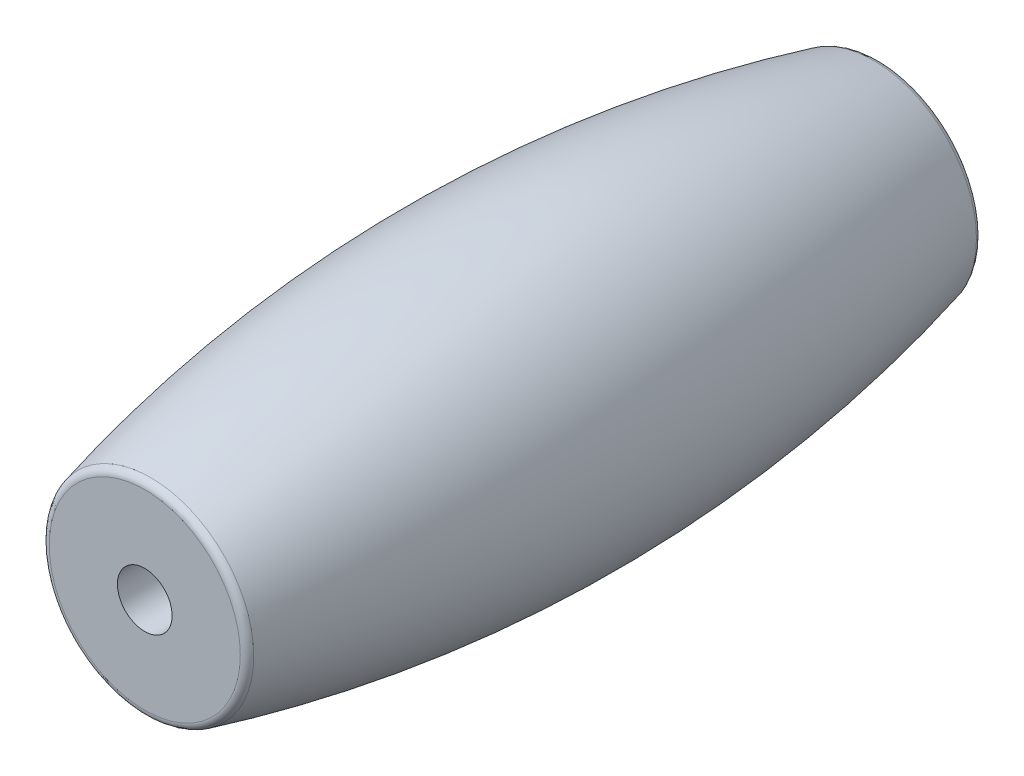
SolidWorks part; units mm, degrees
material "Silicon Rubber"
ref_plane "Front Plane" through (0, 0, 0) normal (0, 0, 1) x (1, 0, 0)
ref_plane "Top Plane" through (0, 0, 0) normal (0, 1, 0) x (1, 0, 0)
ref_plane "Right Plane" through (0, 0, 0) normal (1, 0, 0) x (0, 0, -1)
sketch "Sketch1" plane through (0, 0, 0) normal (0, 1, 0) x (1, 0, 0)
  line L0 (0, 14.828) -> (0, -32.172)
  line L1 (0, 14.828) -> (6.5, 14.828)
  line L2 (0, -32.172) -> (6.5, -32.172)
  arc A0 (6.5, 14.828) -> (6.5, -32.172) centre (-84.0417, -8.672) cw
  point P6 (9.5, -8.672)
  dimension "D1" = 6.5
  dimension "D2" = 9.5
  dimension "D3" = 47
revolve "Revolve1" add sketch "Sketch1" angle 360 about L0
sketch "Sketch2" plane through (0, 0, 32.172) normal (0, 0, 1) x (1, 0, 0)
  circle A0 centre (0, 0) radius 1.75
  dimension "D1" = 3.5
extrude "Cut-Extrude1" cut sketch "Sketch2" against normal through all
fillet "Fillet1" radius 0.5 2 edges at (-6.5, 0, 32.172) (-6.5, 0, -14.828)
